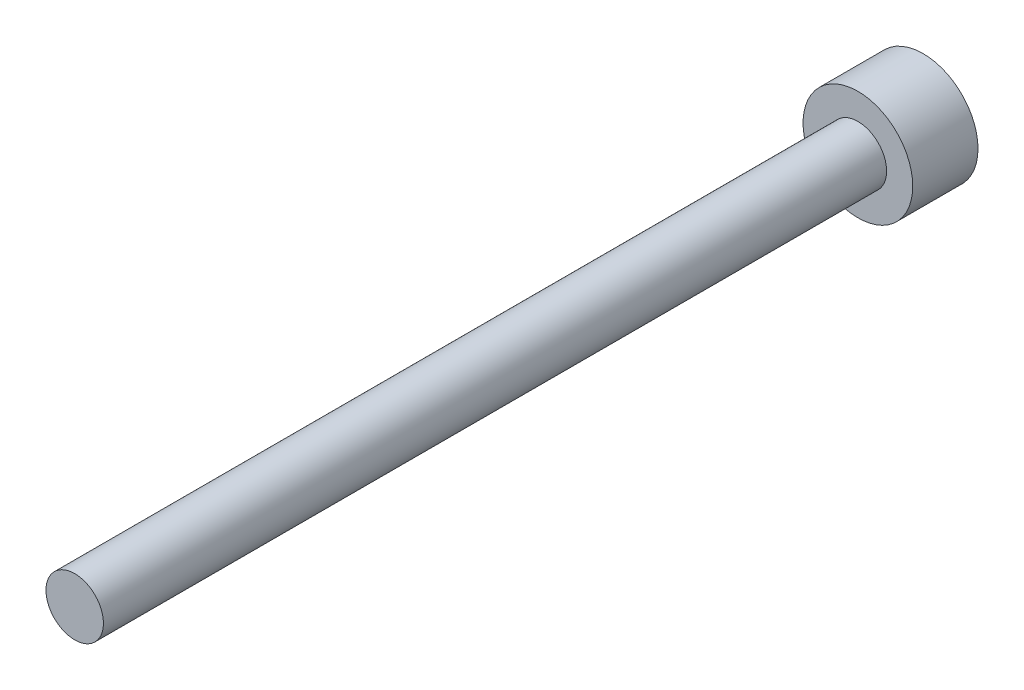
SolidWorks part; units mm, degrees
material "1060 Alloy"
ref_plane "Front Plane" through (0, 0, 0) normal (0, 0, 1) x (1, 0, 0)
ref_plane "Top Plane" through (0, 0, 0) normal (0, 1, 0) x (1, 0, 0)
ref_plane "Right Plane" through (0, 0, 0) normal (1, 0, 0) x (0, 0, -1)
sketch "Sketch1" plane through (0, 0, 0) normal (0, 0, 1) x (1, 0, 0)
  circle A0 centre (0, 0) radius 5.334
  dimension "D1" = 10.668
extrude "Boss-Extrude1" add sketch "Sketch1" along normal blind 6.35
sketch "Sketch3" plane through (0, 0, 6.35) normal (0, 0, 1) x (1, 0, 0)
  circle A0 centre (0, 0) radius 2.794
  dimension "D1" = 5.588
extrude "Boss-Extrude2" add sketch "Sketch3" along normal blind 76.2
